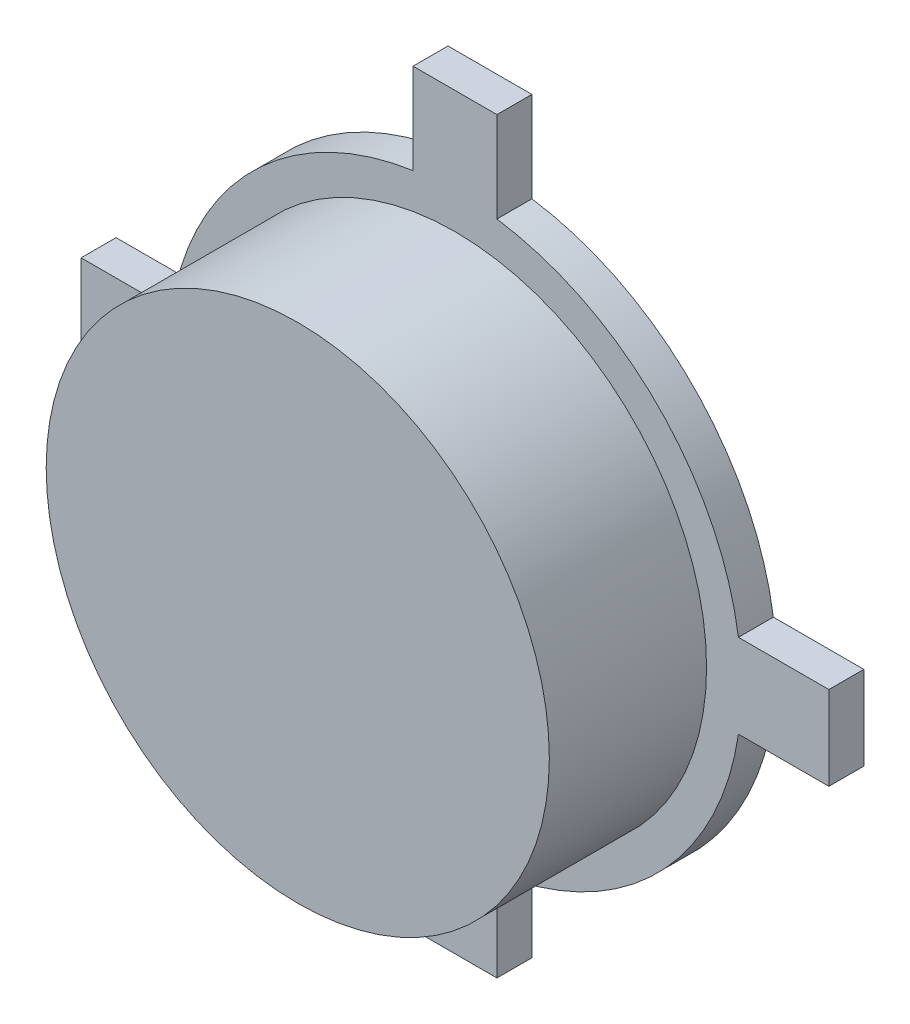
SolidWorks part; units mm, degrees
ref_plane "Front Plane" through (0, 0, 0) normal (0, 0, 1) x (1, 0, 0)
ref_plane "Top Plane" through (0, 0, 0) normal (0, 1, 0) x (1, 0, 0)
ref_plane "Right Plane" through (0, 0, 0) normal (1, 0, 0) x (0, 0, -1)
sketch "Sketch1" plane through (0, 0, 0) normal (0, 0, 1) x (1, 0, 0)
  circle A0 centre (0, 0) radius 7.2
  circle A1 centre (0, 0) radius 7.5 construction
  dimension "D1" = 0.3
extrude "Boss-Extrude1" add sketch "Sketch1" along normal blind 4.5
sketch "Sketch4" plane through (0, 0, 0) normal (0, 0, -1) x (-1, 0, 0)
  line L110 (10.7, 1.2) -> (8.1117, 1.2)
  line L111 (10.7, -1.2) -> (10.7, 1.2)
  line L112 (8.1117, -1.2) -> (10.7, -1.2)
  line L113 (1.2, -10.7) -> (1.2, -8.1117)
  line L114 (-1.2, -10.7) -> (1.2, -10.7)
  line L115 (-1.2, -8.1117) -> (-1.2, -10.7)
  line L116 (-10.7, -1.2) -> (-8.1117, -1.2)
  line L117 (-10.7, 1.2) -> (-10.7, -1.2)
  line L118 (-8.1117, 1.2) -> (-10.7, 1.2)
  line L119 (-1.2, 10.7) -> (-1.2, 8.1117)
  line L120 (1.2, 8.1117) -> (1.2, 10.7)
  line L121 (1.2, 10.7) -> (-1.2, 10.7)
  line L122 (10.7, 1.2) -> (8.1117, 1.2)
  line L123 (10.7, -1.2) -> (10.7, 1.2)
  line L124 (8.1117, -1.2) -> (10.7, -1.2)
  line L125 (1.2, -10.7) -> (1.2, -8.1117)
  line L126 (-1.2, -10.7) -> (1.2, -10.7)
  line L127 (-1.2, -8.1117) -> (-1.2, -10.7)
  line L128 (-10.7, -1.2) -> (-8.1117, -1.2)
  line L129 (-10.7, 1.2) -> (-10.7, -1.2)
  line L130 (-8.1117, 1.2) -> (-10.7, 1.2)
  line L131 (-1.2, 10.7) -> (-1.2, 8.1117)
  line L132 (1.2, 8.1117) -> (1.2, 10.7)
  line L133 (1.2, 10.7) -> (-1.2, 10.7)
  arc A42 (1.2, -8.1117) -> (8.1117, -1.2) centre (0, 0) ccw
  arc A43 (-8.1117, -1.2) -> (-1.2, -8.1117) centre (0, 0) ccw
  arc A44 (-1.2, 8.1117) -> (-8.1117, 1.2) centre (0, 0) ccw
  arc A45 (8.1117, 1.2) -> (1.2, 8.1117) centre (0, 0) ccw
  arc A46 (1.2, -8.1117) -> (8.1117, -1.2) centre (0, 0) ccw
  arc A47 (-8.1117, -1.2) -> (-1.2, -8.1117) centre (0, 0) ccw
  arc A48 (-1.2, 8.1117) -> (-8.1117, 1.2) centre (0, 0) ccw
  arc A49 (8.1117, 1.2) -> (1.2, 8.1117) centre (0, 0) ccw
  dimension "D1" = 0.3
extrude "Boss-Extrude3" add sketch "Sketch4" along normal blind 1
